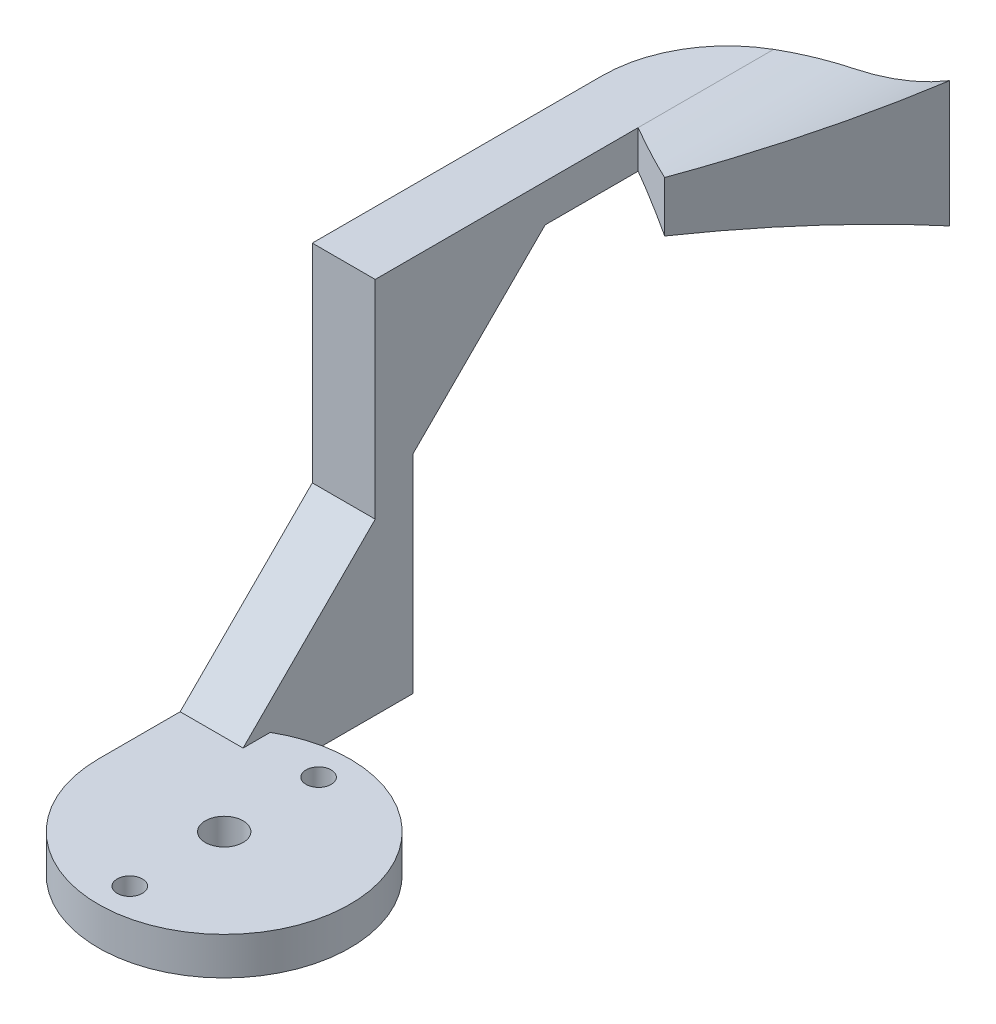
SolidWorks part; units mm, degrees
ref_plane "Front Plane" through (0, 0, 0) normal (0, 0, 1) x (1, 0, 0)
ref_plane "Top Plane" through (0, 0, 0) normal (0, 1, 0) x (1, 0, 0)
ref_plane "Right Plane" through (0, 0, 0) normal (1, 0, 0) x (0, 0, -1)
sketch "Sketch1" plane through (0, 0, 0) normal (0, 1, 0) x (1, 0, 0)
  line L0 (-10, 0) -> (-10, 20)
  line L1 (-10, 20) -> (-5, 20)
  line L2 (-5, 20) -> (-5, 8.6603)
  arc A0 (-10, 0) -> (-5, 8.6603) centre (0, 0) ccw
  circle A1 centre (0, 0) radius 1.5
  dimension "D1" = 20
  dimension "D4" = 3
  dimension "D2" = 5
  dimension "D3" = 20
extrude "Boss-Extrude1" add sketch "Sketch1" along normal blind 3
sketch "Sketch2" plane through (-10, 0, 0) normal (-1, 0, 0) x (0, 0, 1)
  line L0 (-8.6603, 0) -> (-20, 0) construction
  line L1 (-17, 0) -> (-20, 0)
  line L2 (-17, 13.5) -> (-17, 30)
  line L3 (-17, 30) -> (-20, 30)
  line L4 (-20, 0) -> (-20, 16.5)
  line L5 (-30.5, 27) -> (-20, 16.5)
  line L6 (-17, 30) -> (-30, 30)
  line L7 (-17, 30) -> (-17, 13.5)
  line L8 (-30.5, 27) -> (-30, 27)
  line L9 (-30, 30) -> (-30, 27)
  line L10 (-8.6603, 3) -> (-20, 3) construction
  line L11 (-18.5, 0) -> (-18.5, 30) construction
  line L12 (-17, 13.5) -> (-6.5, 3)
  line L13 (-30, 30) -> (-20, 30)
  line L14 (-6.5, 3) -> (-6.5, 0)
  line L15 (-6.5, 0) -> (-17, 0)
  point P19 (-18.5, 15)
  line M9 (-20, 0) -> (0, 0)
  line M11 (0, 3) -> (-20, 3)
  line M12 (-20, 3) -> (-20, 0)
  dimension "D1" = 3
  dimension "D2" = 3
  dimension "D3" = 30
  dimension "D4" = 30
  dimension "D5" = 45
extrude "Boss-Extrude2" add sketch "Sketch2" against normal blind 5 contours L11 M9 M11 M12 | L11 L1 L14 M9 M11 | L11 L12 L2 L3 M11 | L11 L6 L9 L8 L5 L4 M11
sketch "Sketch4" plane through (0, 30, 0) normal (0, 1, 0) x (1, 0, 0)
  line L0 (-5, 17) -> (-10, 17)
  line L1 (-10, 17) -> (-10, 40)
  line L3 (0, 50) -> (0, 35)
  line L4 (0, 35) -> (-5, 37.8868)
  line L5 (-5, 37.8868) -> (-5, 30)
  line L9 (-10, 30) -> (-10, 17)
  line L10 (-10, 17) -> (-5, 17)
  line L11 (-5, 17) -> (-5, 30)
  line L12 (-5, 30) -> (-10, 30)
  line L15 (-5, 17) -> (-5, 30)
  arc A0 (-10, 40) -> (0, 50) centre (0, 40) cw
  dimension "D1" = 60
  dimension "D2" = 5
  dimension "D3" = 15
  dimension "D4" = 50
  dimension "D5" = 0
extrude "Boss-Extrude3" add sketch "Sketch4" against normal up to surface (3 mm away) up to face at (-7.5, 27, -30.25)
sketch "Sketch5" plane through (0, 30, 0) normal (0, 1, 0) x (1, 0, 0)
  line L0 (-5, 37.8868) -> (-10, 37.8868)
  line L1 (-10, 17) -> (-10, 40) construction
  line L2 (-10, 37.8868) -> (-10, 40)
  line L4 (0, 35) -> (-5, 37.8868)
  line L6 (0, 35) -> (0, 50) construction
  line L7 (0, 50) -> (7.6429, 50)
  line L8 (7.6429, 50) -> (0, 35)
  arc A0 (-10, 40) -> (0, 50) centre (0, 40) cw
  dimension "D1" = 27
extrude "Boss-Extrude4" add sketch "Sketch5" along normal mid plane 10 from offset 1.5 offset against normal yes
ref_plane "Plane1" through (0, 0, -35) normal (0, 0, -1) x (-1, 0, 0)
sketch "Sketch6" plane through (0, 0, -35) normal (0, 0, 1) x (1, 0, 0)
  line L0 (-10, 30) -> (-5, 30)
  line L1 (7.6429, 33.5) -> (7.6429, 23.5)
  line L2 (7.6429, 28.5) -> (-10, 28.5) construction
  line L3 (-10, 13.5) -> (-10, 30) construction
  line L4 (-10, 27) -> (-5, 27)
  line L5 (-10, 27) -> (-10, 30)
  arc A0 (-5, 30) -> (7.6429, 33.5) centre (-5, 54.5846) ccw
  arc A1 (-5, 27) -> (7.6429, 23.5) centre (-5, 2.4154) cw
extrude "Cut-Extrude2" cut sketch "Sketch6" against normal through all flip side to cut
ref_plane "Plane2" through (0, 28.5, 0) normal (0, 1, 0) x (1, 0, 0)
sketch "Sketch7" plane through (0, 0, 0) normal (0, -1, 0) x (1, 0, 0)
  line L0 (0, 7.5) -> (0, -7.5) construction
  circle A0 centre (0, -7.5) radius 1
  circle A1 centre (0, 7.5) radius 1
  point P4 (0, 0)
  dimension "D1" = 15
  dimension "D2" = 2
extrude "Cut-Extrude3" cut sketch "Sketch7" against normal through all
